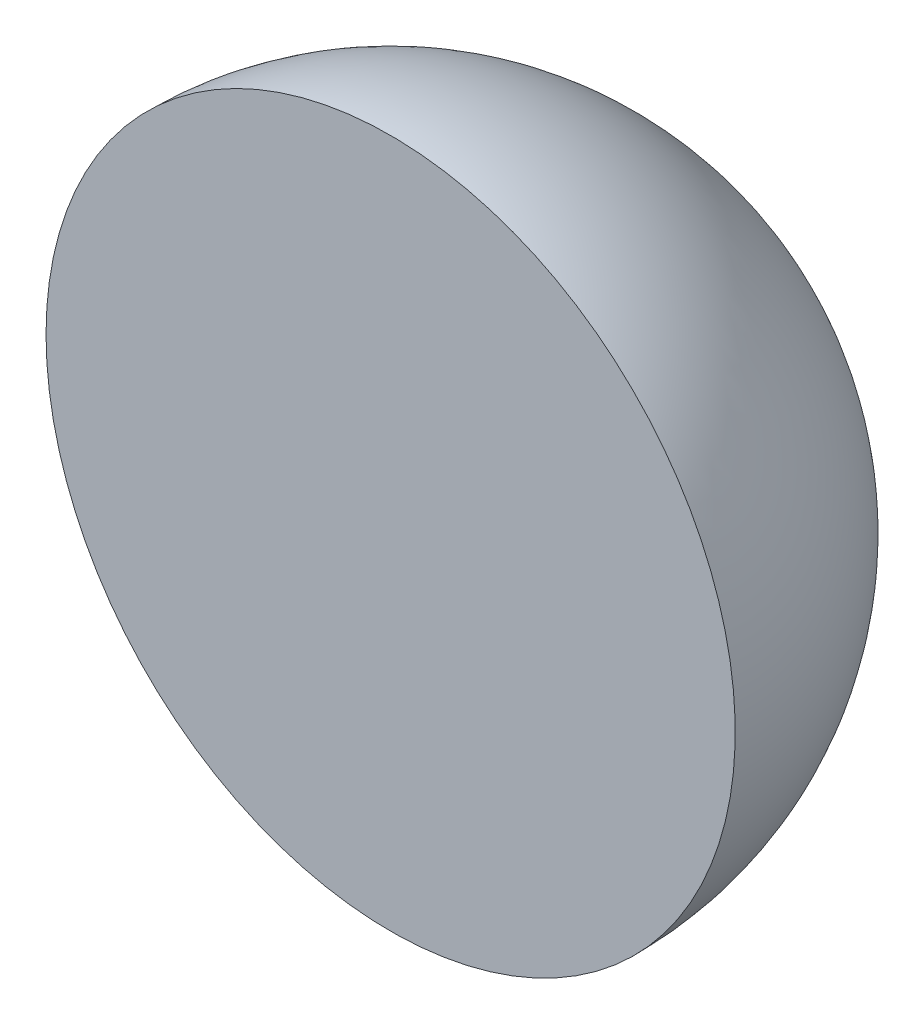
SolidWorks part; units mm, degrees
ref_plane "正面" through (0, 0, 0) normal (0, 0, 1) x (1, 0, 0)
ref_plane "平面" through (0, 0, 0) normal (0, 1, 0) x (1, 0, 0)
ref_plane "右側面" through (0, 0, 0) normal (1, 0, 0) x (0, 0, -1)
sketch "ｽｹｯﾁ1" plane through (0, 0, 0) normal (0, 1, 0) x (1, 0, 0)
  line L1 (4.9999, 0.0001) -> (-5.0001, 0.0001)
  line L3 (-0.0001, 4.9999) -> (-0.0001, 0.0001) construction
  arc A0 (4.9999, 0.0001) -> (-4.9999, 0) centre (0, 0) ccw
  point P5 (0, 0)
  point P8 (0, 0)
  point P9 (0, 0)
  point P10 (0, 0)
  point P11 (0, 0)
  dimension "D1" = 4.9999
  dimension "D2" = 10
  dimension "D3" = 4.9998
revolve "回転2" add sketch "ｽｹｯﾁ1" angle 360 about L3
